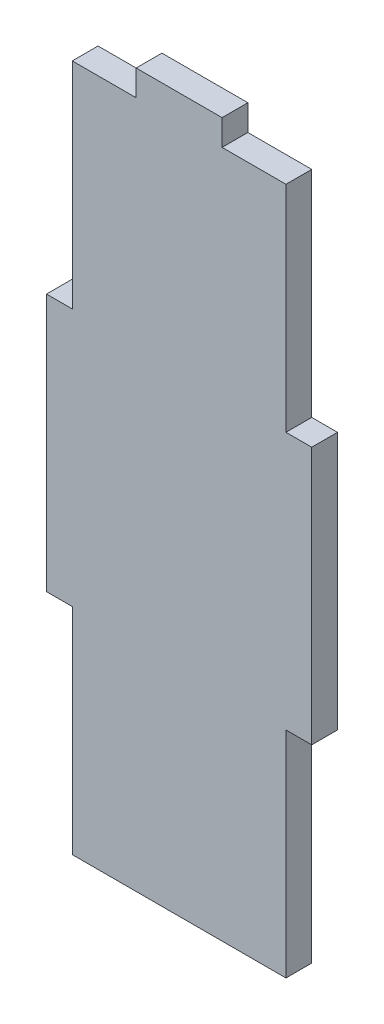
SolidWorks part; units mm, degrees
ref_plane "前视基准面" through (0, 0, 0) normal (0, 0, 1) x (1, 0, 0)
ref_plane "上视基准面" through (0, 0, 0) normal (0, 1, 0) x (1, 0, 0)
ref_plane "右视基准面" through (0, 0, 0) normal (1, 0, 0) x (0, 0, -1)
sketch "草图1" plane through (0, 0, 0) normal (0, 0, 1) x (1, 0, 0)
  line L0 (0, -40) -> (24.87, -40)
  line L1 (0, 0) -> (24.87, 0)
  line L2 (0, 0) -> (0, -80)
  line L3 (0, -80) -> (24.87, -80)
  line L4 (24.87, 0) -> (24.87, -80)
  line L5 (12.435, 0) -> (12.435, -80)
  line L6 (24.87, -55) -> (27.87, -55)
  line L7 (0, -25) -> (-3, -25)
  line L8 (0, -25) -> (0, -55)
  line L9 (0, -55) -> (-3, -55)
  line L10 (-3, -25) -> (-3, -55)
  line L11 (27.87, -25) -> (27.87, -55)
  line L12 (24.87, -25) -> (27.87, -25)
  line L13 (24.87, -25) -> (24.87, -55)
  line L15 (7.435, 0) -> (17.435, 0)
  line L16 (7.435, 0) -> (7.435, 3)
  line L17 (7.435, 3) -> (17.435, 3)
  line L18 (17.435, 0) -> (17.435, 3)
  dimension "D1" = 24.87
  dimension "D2" = 80
  dimension "D3" = 30
  dimension "D4" = 3
  dimension "D5" = 15
  dimension "D6" = 3
  dimension "D7" = 10
  dimension "D8" = 5
extrude "凸台-拉伸1" add sketch "草图1" along normal blind 3 contours L5 L1 L2 L0 | L1 L5 L0 L4 | L0 L5 L3 L4 | L5 L0 L2 L3 | L7 L10 L9 L2 | L1 L18 L17 L16 | L12 L4 L6 L11
